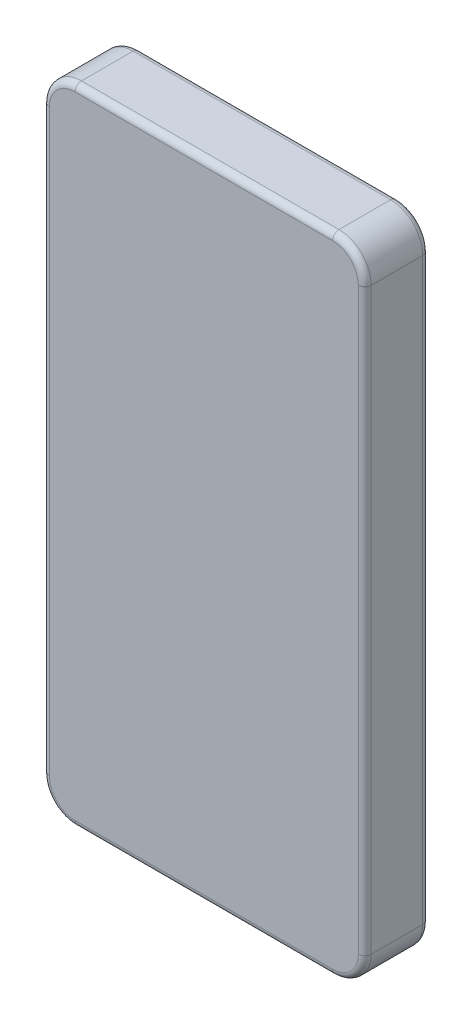
SolidWorks part; units mm, degrees
ref_plane "Alzado" through (0, 0, 0) normal (0, 0, 1) x (1, 0, 0)
ref_plane "Planta" through (0, 0, 0) normal (0, 1, 0) x (1, 0, 0)
ref_plane "Vista lateral" through (0, 0, 0) normal (1, 0, 0) x (0, 0, -1)
sketch "Croquis1" plane through (0, 0, 0) normal (0, 0, 1) x (1, 0, 0)
  line L0 (-0.25, 0.5) -> (0.25, -0.5) construction
  line L1 (-0.25, 0.5) -> (0.25, 0.5)
  line L2 (-0.25, 0.5) -> (-0.25, -0.5)
  line L3 (-0.25, -0.5) -> (0.25, -0.5)
  line L4 (0.25, 0.5) -> (0.25, -0.5)
  line L5 (0.25, 0.5) -> (-0.25, -0.5) construction
  dimension "D1" = 1
  dimension "D2" = 0.5
extrude "Saliente-Extruir1" add sketch "Croquis1" along normal mid plane 0.1
fillet "Redondeo3" radius 0.05 4 edges at (-0.25, -0.5, 0) (0.25, -0.5, 0) (-0.25, 0.5, 0) (0.25, 0.5, 0)
fillet "Redondeo4" radius 0.01 16 edges at (0.2354, -0.4854, -0.05) (0.25, 0, -0.05) (0.2354, 0.4854, -0.05) (0, 0.5, -0.05) (-0.2354, 0.4854, -0.05) (-0.25, 0, -0.05) (-0.2354, -0.4854, -0.05) (0, -0.5, -0.05) (-0.2354, 0.4854, 0.05) (0, 0.5, 0.05) (0.2354, 0.4854, 0.05) (0.25, 0, 0.05) (0.2354, -0.4854, 0.05) (0, -0.5, 0.05) (-0.2354, -0.4854, 0.05) (-0.25, 0, 0.05)
